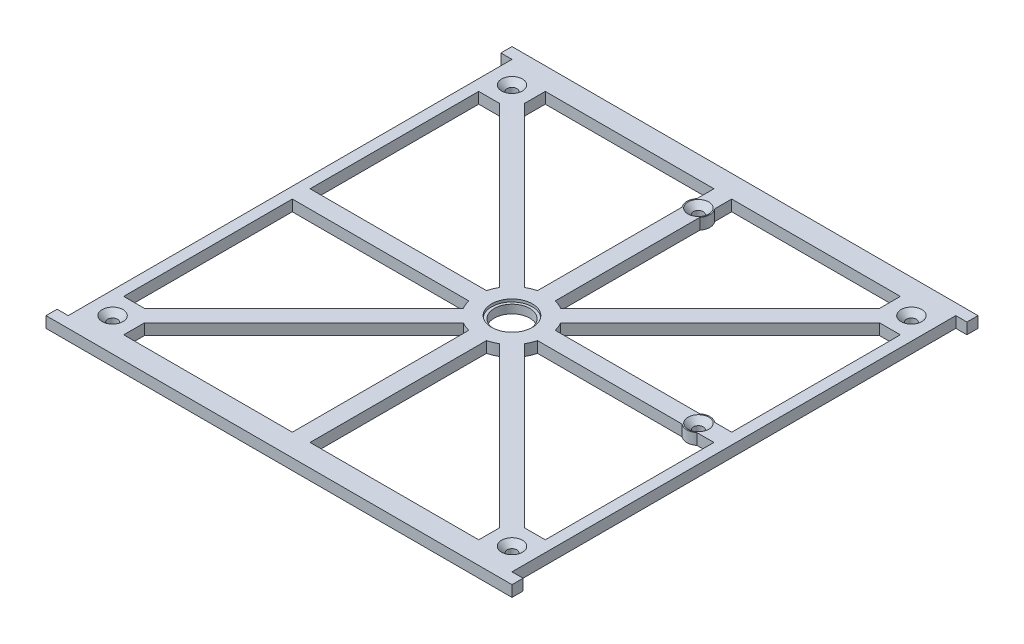
SolidWorks part; units mm, degrees
ref_plane "Front Plane" through (0, 0, 0) normal (0, 0, 1) x (1, 0, 0)
ref_plane "Top Plane" through (0, 0, 0) normal (0, 1, 0) x (1, 0, 0)
ref_plane "Right Plane" through (0, 0, 0) normal (1, 0, 0) x (0, 0, -1)
sketch "Sketch1" plane through (0, 0, 0) normal (0, 1, 0) x (1, 0, 0)
  line L873 (52.5, -52.5) -> (-52.5, -52.5) construction
  line L874 (52.5, -52.5) -> (52.5, 52.5) construction
  line L875 (52.5, 52.5) -> (-52.5, 52.5) construction
  line L876 (-52.5, -52.5) -> (-52.5, 52.5) construction
  line L877 (52.5, -52.5) -> (-52.5, 52.5) construction
  line L878 (52.5, 52.5) -> (-52.5, -52.5) construction
  line L880 (-50, 50) -> (50, 50) construction
  line L881 (-50, 50) -> (-50, -50) construction
  line L882 (-50, -50) -> (50, -50) construction
  line L883 (50, 50) -> (50, -50) construction
  line L884 (-52.5, 0) -> (52.5, 0) construction
  line L886 (0, 52.5) -> (0, -52.5) construction
  line L979 (-40, 47.5) -> (40, 47.5)
  line L982 (-47.5, -40) -> (-47.5, 40)
  line L997 (-50, 52.5) -> (50, 52.5)
  line L998 (-50, -52.5) -> (50, -52.5)
  line L1004 (-47.5, 40) -> (-40, 40)
  line L1007 (-40, 40) -> (-40, 47.5)
  line L1008 (-45, 45) -> (-40, 45) construction
  line L1009 (-45, 45) -> (-45, 40) construction
  line L1011 (47.5, -40) -> (47.5, 40)
  line L1012 (40, 40) -> (40, 47.5)
  line L1013 (50, 52.5) -> (50, -52.5)
  line L1014 (-50, -52.5) -> (-50, 52.5)
  line L1017 (47.5, 40) -> (40, 40)
  line L1019 (47.5, -40) -> (40, -40)
  line L1020 (-47.5, -40) -> (-40, -40)
  line L1025 (-40, -40) -> (-40, -47.5)
  line L1026 (-40, -47.5) -> (40, -47.5)
  line L1027 (40, -40) -> (40, -47.5)
  circle A150 centre (-45, 45) radius 1.1
  circle A168 centre (45, 45) radius 1.1
  circle A169 centre (45, -45) radius 1.1
  circle A170 centre (-45, -45) radius 1.1
  point P0 (0, 0)
  point P13 (-50, 0)
  point P36 (0, 50)
  point P48 (0, 47.5)
  point P50 (0, 0)
  dimension "D6" = 2.5
  dimension "D2" = 100
  dimension "D3" = 45
  dimension "D4" = 2.2
  dimension "D1" = 105
  dimension "D9" = 5
  dimension "D10" = 5
extrude "Boss-Extrude1" add sketch "Sketch1" along normal blind 2.5
sketch "Sketch3" plane through (0, 0, 0) normal (0, 1, 0) x (1, 0, 0)
  line L989 (-42.8284, 40) -> (-6.8914, 4.063)
  line L1008 (0, 52.5) -> (0, -52.5) construction
  line L1009 (50, 52.5) -> (-50, 52.5) construction
  line L1026 (-45, 45) -> (45, -45) construction
  line L1028 (-45, -45) -> (45, 45) construction
  line L1029 (-40, 42.8284) -> (-4.063, 6.8914)
  line L1030 (-40, 47.5) -> (-40, 40) construction
  line L1031 (-9.0858, 11.9142) -> (-11.9142, 9.0858) construction
  line L1032 (-40, 40) -> (-47.5, 40) construction
  line L1033 (-50, -52.5) -> (50, -52.5) construction
  line L1034 (-42.8284, 40) -> (-40, 42.8284)
  line L1035 (-2, 47.5) -> (-2, 43.6613)
  line L1036 (40, 47.5) -> (-40, 47.5) construction
  line L1037 (2, 47.5) -> (2, 43.6613)
  line L1038 (-2, 16) -> (2, 16) construction
  line L1039 (-2, 47.5) -> (2, 47.5)
  line L1040 (40, 42.8284) -> (4.063, 6.8914)
  line L1041 (40, 42.8284) -> (42.8284, 40)
  line L1042 (42.8284, 40) -> (6.8914, 4.063)
  line L1043 (47.5, 2) -> (43.6613, 2)
  line L1044 (47.5, 2) -> (47.5, -2)
  line L1045 (47.5, -2) -> (43.6613, -2)
  line L1046 (42.8284, -40) -> (6.8914, -4.063)
  line L1047 (42.8284, -40) -> (40, -42.8284)
  line L1048 (40, -42.8284) -> (4.063, -6.8914)
  line L1049 (2, -47.5) -> (2, -43.6613)
  line L1050 (2, -47.5) -> (-2, -47.5)
  line L1051 (-2, -47.5) -> (-2, -43.6613)
  line L1052 (-40, -42.8284) -> (-4.063, -6.8914)
  line L1053 (-40, -42.8284) -> (-42.8284, -40)
  line L1054 (-42.8284, -40) -> (-6.8914, -4.063)
  line L1055 (-47.5, -2) -> (-43.6613, -2)
  line L1056 (-47.5, -2) -> (-47.5, 2)
  line L1057 (-47.5, 2) -> (-40.3387, 2)
  line L1058 (-40.3387, 2) -> (-7.746, 2)
  line L1059 (-43.6613, -2) -> (-7.746, -2)
  line L1060 (-2, -43.6613) -> (-2, -7.746)
  line L1061 (2, -43.6613) -> (2, -7.746)
  line L1062 (40.3387, 2) -> (7.746, 2)
  line L1063 (40.3387, -2) -> (7.746, -2)
  line L1064 (-2, 40.3387) -> (-2, 7.746)
  line L1065 (2, 40.3387) -> (2, 7.746)
  circle A152 centre (0, 0) radius 4
  circle A171 centre (0, 0) radius 4.6 construction
  arc A172 (-7.746, -2) -> (-6.8914, -4.063) centre (0, 0) ccw
  arc A173 (7.746, 2) -> (6.8914, 4.063) centre (0, 0) ccw
  arc A174 (-6.8914, 4.063) -> (-7.746, 2) centre (0, 0) ccw
  arc A175 (-2, 7.746) -> (-4.063, 6.8914) centre (0, 0) ccw
  arc A176 (4.063, 6.8914) -> (2, 7.746) centre (0, 0) ccw
  arc A177 (6.8914, -4.063) -> (7.746, -2) centre (0, 0) ccw
  arc A178 (2, -7.746) -> (4.063, -6.8914) centre (0, 0) ccw
  arc A179 (-4.063, -6.8914) -> (-2, -7.746) centre (0, 0) ccw
  circle A180 centre (0, 42) radius 1.1
  circle A181 centre (42, 0) radius 1.1
  arc A185 (2, 40.3387) -> (2, 43.6613) centre (0, 42) ccw
  arc A186 (40.3387, -2) -> (43.6613, -2) centre (42, 0) ccw
  arc A191 (43.6613, 2) -> (40.3387, 2) centre (42, 0) ccw
  circle A192 centre (0, 42) radius 2.6 construction
  arc A193 (-2, 43.6613) -> (-2, 40.3387) centre (0, 42) ccw
  circle A194 centre (-42, 0) radius 1.1 [skipped]
  circle A195 centre (0, -42) radius 1.1 [skipped]
  arc A196 (-2, -40.3387) -> (-2, -43.6613) centre (0, -42) ccw [skipped]
  arc A197 (-43.6613, -2) -> (-40.3387, -2) centre (-42, 0) ccw [skipped]
  point P16 (0, 0)
  point P21 (-10.5, 10.5)
  point P34 (0, 16)
  point P50 (0, 0)
  point P68 (0, 0)
  point P76 (0, 0)
  dimension "D5" = 8
  dimension "D6" = 42
  dimension "D8" = 9.2
  dimension "D7" = 4
  dimension "D2" = 16
  dimension "D3" = 4
  dimension "D4" = 2.2
  dimension "D9" = 1.5
  dimension "D1" = 4
extrude "Boss-Extrude2" add sketch "Sketch3" along normal up to surface (2.5 mm away) up to face at (45, 2.5, 46.1)
chamfer "Chamfer1" distance 1.25 angle 45 6 edges at (45, 2.5, -46.1) (45, 2.5, 46.1) (-45, 2.5, 43.9) (-45, 2.5, -43.9) (42, 2.5, 1.1) (0, 2.5, -40.9)
sketch "Sketch2" plane through (0, 2.5, 0) normal (0, 1, 0) x (1, 0, 0)
  circle A0 centre (0, 0) radius 4.6
  dimension "D1" = 9.2
extrude "Cut-Extrude1" cut sketch "Sketch2" against normal blind 0.6
sketch "Sketch11" plane through (0, 2.5, 0) normal (0, 1, 0) x (1, 0, 0)
  line L1 (-50, 52.5) -> (-52.5, 52.5)
  line L2 (-50, 52.5) -> (-50, 50)
  line L3 (-50, 50) -> (-52.5, 50)
  line L4 (-52.5, 52.5) -> (-52.5, 50)
  line L5 (50, 52.5) -> (52.5, 52.5)
  line L6 (50, 52.5) -> (50, 50)
  line L7 (50, 50) -> (52.5, 50)
  line L8 (52.5, 52.5) -> (52.5, 50)
  line L9 (-50, -52.5) -> (-52.5, -52.5)
  line L10 (-50, -52.5) -> (-50, -50)
  line L11 (-50, -50) -> (-52.5, -50)
  line L12 (-52.5, -52.5) -> (-52.5, -50)
  line L13 (50, -52.5) -> (52.5, -52.5)
  line L14 (50, -52.5) -> (50, -50)
  line L15 (50, -50) -> (52.5, -50)
  line L16 (52.5, -52.5) -> (52.5, -50)
  dimension "D1" = 2.5
  dimension "D2" = 2.5
extrude "Boss-Extrude5" add sketch "Sketch11" against normal up to surface (2.5 mm away) up to face at (33.7912, 0, -13.2419)
